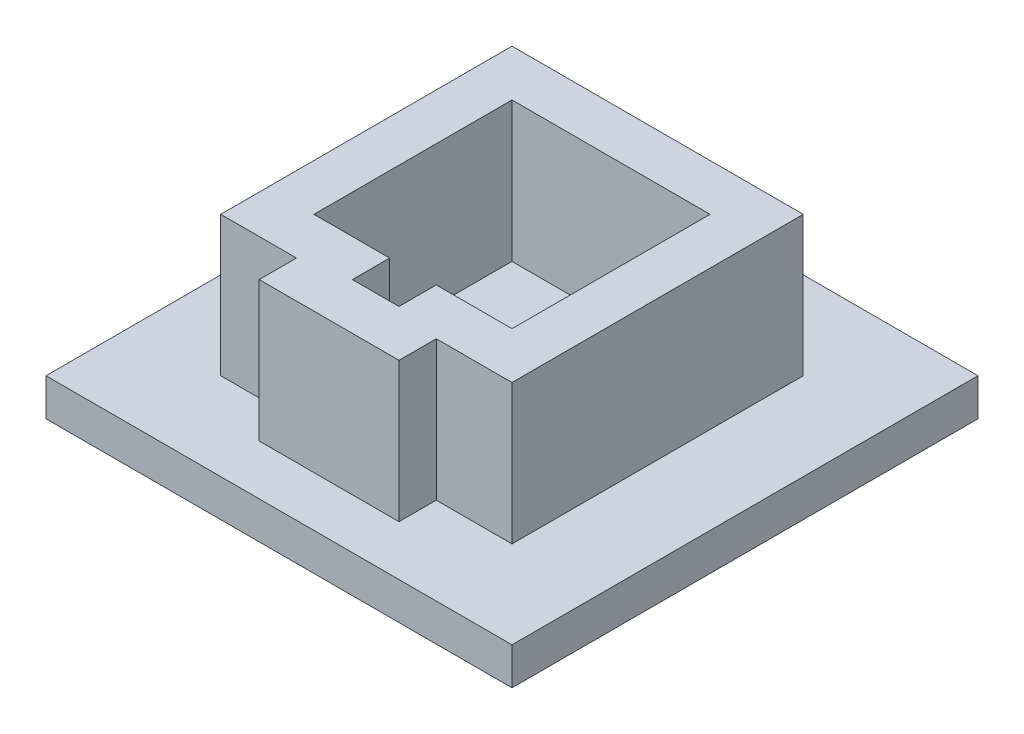
SolidWorks part; units mm, degrees
ref_plane "Ön Düzlem" through (0, 0, 0) normal (0, 0, 1) x (1, 0, 0)
ref_plane "Üst Düzlem" through (0, 0, 0) normal (0, 1, 0) x (1, 0, 0)
ref_plane "Sağ Düzlem" through (0, 0, 0) normal (1, 0, 0) x (0, 0, -1)
sketch "Çizim1" plane through (0, 0, 0) normal (0, 1, 0) x (1, 0, 0)
  line L1 (0, 0) -> (100, 0)
  line L2 (0, 0) -> (0, 100)
  line L3 (0, 100) -> (100, 100)
  line L4 (100, 0) -> (100, 100)
  dimension "D1" = 100
  dimension "D2" = 100
extrude "Yükseklik-Ekstrüzyon1" add sketch "Çizim1" along normal blind 8
sketch "Çizim2" plane through (0, 8, 0) normal (0, 1, 0) x (1, 0, 0)
  line L0 (55, 28.75) -> (71.25, 28.75)
  line L1 (0, 0) -> (100, 0)
  line L2 (0, 0) -> (0, 100)
  line L3 (0, 100) -> (100, 100)
  line L4 (100, 0) -> (100, 100)
  line L5 (28.75, 71.25) -> (71.25, 71.25)
  line L6 (28.75, 71.25) -> (28.75, 28.75)
  line L7 (28.75, 28.75) -> (45, 28.75)
  line L8 (71.25, 71.25) -> (71.25, 28.75)
  line L10 (45, 28.75) -> (45, 20.75)
  line L11 (45, 20.75) -> (55, 20.75)
  line L12 (55, 28.75) -> (55, 20.75)
  dimension "D1" = 42.5
  dimension "D2" = 28.75
  dimension "D3" = 28.75
  dimension "D4" = 10
  dimension "D5" = 8
  dimension "D6" = 16.25
extrude "Yükseklik-Ekstrüzyon2" add sketch "Çizim2" along normal blind 30
sketch "Çizim3" plane through (0, 38, 0) normal (0, 1, 0) x (1, 0, 0)
  line L0 (71.25, 28.75) -> (71.25, 71.25) construction
  line L1 (18.75, 81.25) -> (81.25, 81.25)
  line L2 (18.75, 81.25) -> (18.75, 18.75)
  line L3 (18.75, 18.75) -> (35, 18.75)
  line L4 (81.25, 81.25) -> (81.25, 18.75)
  line L5 (71.25, 71.25) -> (28.75, 71.25) construction
  line L6 (28.75, 71.25) -> (28.75, 28.75) construction
  line L7 (55, 28.75) -> (71.25, 28.75) construction
  line L8 (35, 18.75) -> (35, 10.75)
  line L9 (35, 10.75) -> (65, 10.75)
  line L10 (65, 10.75) -> (65, 18.75)
  line L11 (65, 18.75) -> (81.25, 18.75)
  line L12 (55, 20.75) -> (55, 28.75) construction
  line L13 (45, 28.75) -> (45, 20.75) construction
  line L14 (45, 20.75) -> (55, 20.75) construction
  line L16 (0, 0) -> (100, 0)
  line L17 (0, 0) -> (0, 100)
  line L18 (0, 100) -> (100, 100)
  line L19 (100, 0) -> (100, 100)
  dimension "D1" = 10
  dimension "D2" = 10
  dimension "D3" = 10
  dimension "D4" = 10
  dimension "D5" = 10
  dimension "D6" = 10
  dimension "D7" = 10
extrude "Kes-Ekstrüzyon1" cut sketch "Çizim3" against normal blind 30
sketch "Çizim4" plane through (0, 8, 0) normal (0, 1, 0) x (1, 0, 0)
  line L0 (0, 100) -> (0, 0) construction
  line L1 (100, 100) -> (0, 100) construction
  line L2 (0, 0) -> (100, 0) construction
  line L3 (100, 0) -> (100, 100) construction
  circle A0 centre (10, 10) radius 1.5
  circle A1 centre (10, 90) radius 1.5
  circle A2 centre (90, 90) radius 1.5
  circle A3 centre (90, 10) radius 1.5
  point P12 (0, 0)
  point P13 (0, 0)
  point P14 (0, 0)
  point P15 (0, 0)
  dimension "D1" = 3
  dimension "D2" = 10
  dimension "D3" = 10
  dimension "D4" = 10
  dimension "D5" = 10
